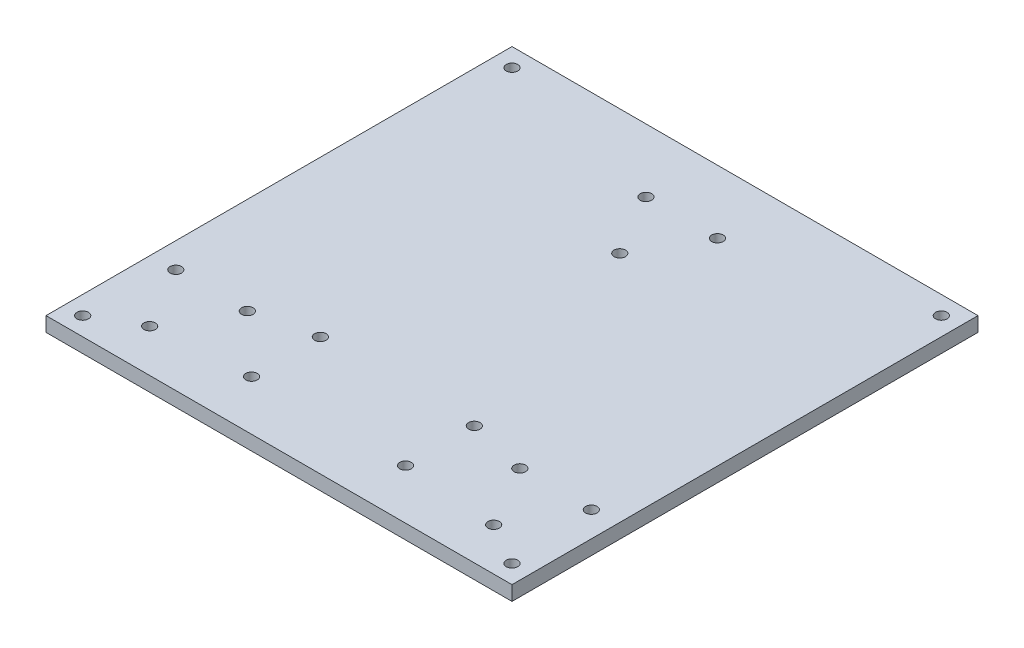
SolidWorks part; units mm, degrees
ref_plane "Plan de face" through (0, 0, 0) normal (0, 0, 1) x (1, 0, 0)
ref_plane "Plan de dessus" through (0, 0, 0) normal (0, 1, 0) x (1, 0, 0)
ref_plane "Plan de droite" through (0, 0, 0) normal (1, 0, 0) x (0, 0, -1)
sketch "Esquisse1" plane through (0, 0, 0) normal (0, 1, 0) x (1, 0, 0)
  line L1 (-101.6, -101.6) -> (101.6, -101.6)
  line L2 (-101.6, -101.6) -> (-101.6, 101.6)
  line L3 (-101.6, 101.6) -> (101.6, 101.6)
  line L4 (101.6, -101.6) -> (101.6, 101.6)
  line L5 (-101.6, -101.6) -> (101.6, 101.6) construction
  line L6 (-101.6, 101.6) -> (101.6, -101.6) construction
  point P0 (0, 0)
  dimension "D1" = 203.2
extrude "Boss.-Extru.1" add sketch "Esquisse1" along normal blind 6.35
sketch "Esquisse2" plane through (0, 6.35, 0) normal (0, 1, 0) x (1, 0, 0)
  circle A0 centre (-33.725, -49.85) radius 2.5
  circle A1 centre (-33.725, -79.85) radius 2.5
  circle A2 centre (33.425, -79.85) radius 2.5
  circle A3 centre (33.425, -49.85) radius 2.5
extrude "Enlèv. mat.-Extru.1" cut sketch "Esquisse2" against normal through all
sketch "Esquisse3" plane through (0, 6.35, 0) normal (0, 1, 0) x (1, 0, 0)
  circle A0 centre (-93.6, 93.6) radius 2.5
  circle A1 centre (93.6, 93.6) radius 2.5
  circle A2 centre (93.6, -93.6) radius 2.5
  circle A3 centre (-93.6, -93.6) radius 2.5
extrude "Enlèv. mat.-Extru.2" cut sketch "Esquisse3" against normal through all
sketch "Esquisse4" plane through (0, 6.35, 0) normal (0, 1, 0) x (1, 0, 0)
  circle A0 centre (-15.5885, 74) radius 2.5
  circle A1 centre (15.5885, 74) radius 2.5
  circle A2 centre (0, 47) radius 2.5
  circle A3 centre (-75, -83) radius 2.5
  circle A4 centre (-90.5885, -56) radius 2.5
  circle A5 centre (-59.4115, -56) radius 2.5
  circle A6 centre (59.4115, -56) radius 2.5
  circle A7 centre (90.5885, -56) radius 2.5
  circle A8 centre (75, -83) radius 2.5
extrude "Enlèv. mat.-Extru.3" cut sketch "Esquisse4" against normal through all
